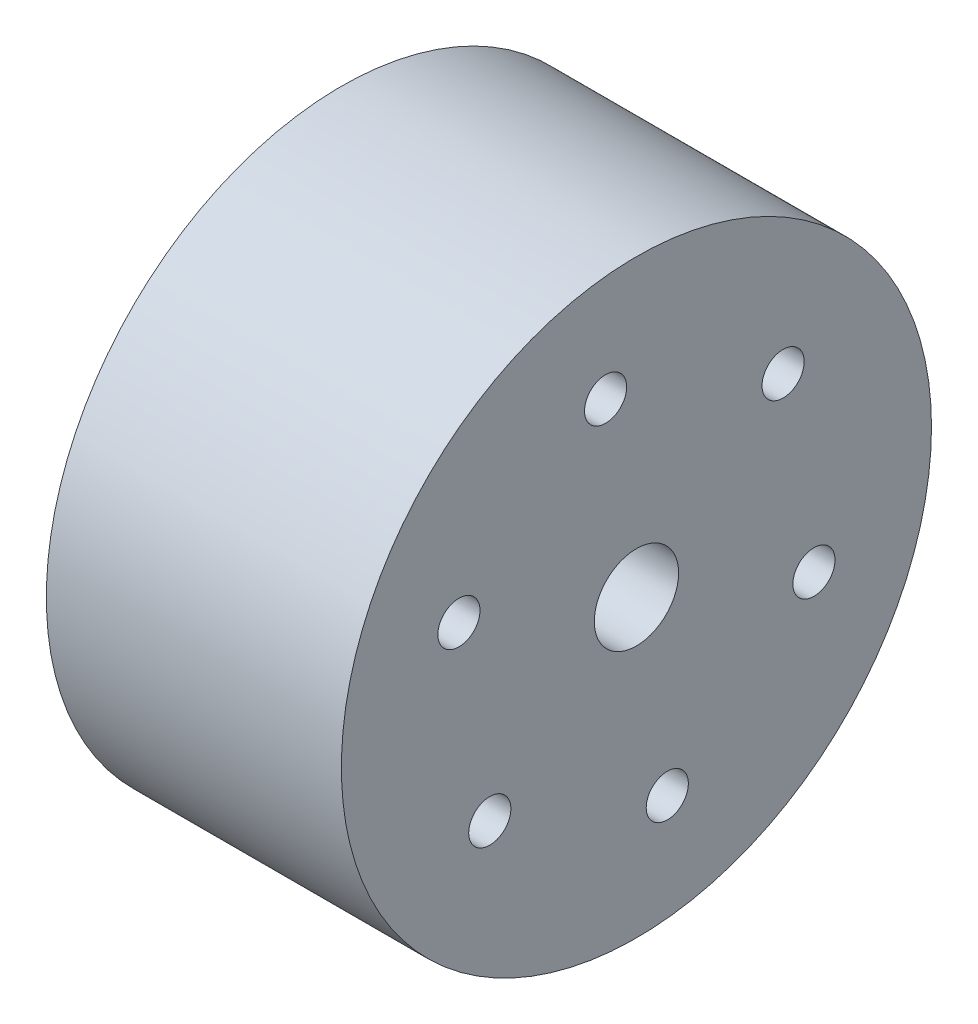
SolidWorks part; units mm, degrees
ref_plane "Front Plane" through (0, 0, 0) normal (0, 0, 1) x (1, 0, 0)
ref_plane "Top Plane" through (0, 0, 0) normal (0, 1, 0) x (1, 0, 0)
ref_plane "Right Plane" through (0, 0, 0) normal (1, 0, 0) x (0, 0, -1)
sketch "Sketch1" plane through (0, 0, 0) normal (0, 0, 1) x (1, 0, 0)
  line L0 (-38.7161, 35) -> (-38.7161, 16)
  line L1 (-38.7161, 16) -> (-33.7161, 16)
  line L2 (-33.7161, 16) -> (-33.7161, 5)
  line L3 (-33.7161, 5) -> (-3.7161, 5)
  line L4 (-3.7161, 5) -> (-3.7161, 35)
  line L5 (-3.7161, 35) -> (-38.7161, 35)
  line L6 (-38.7161, -33) -> (-38.7161, 33) construction
  line L9 (0, 0) -> (-3.7161, 0) construction
  line L10 (-33.7161, -16) -> (-33.7161, 16) construction
  line L13 (0, 0) -> (-58.1661, 0) construction
  dimension "D1" = 35
  dimension "D2" = 30
  dimension "D3" = 32
revolve "Revolve1" add sketch "Sketch1" angle 360 about L9
sketch "Sketch2" plane through (-38.7161, 0, 0) normal (-1, 0, 0) x (0, 0, 1)
  circle A0 centre (21.0557, 7.9314) radius 2.5
  circle A2 centre (17.3966, -14.2691) radius 2.5
  circle A3 centre (-3.6591, -22.2005) radius 2.5
  circle A4 centre (-21.0557, -7.9314) radius 2.5
  circle A5 centre (-17.3966, 14.2691) radius 2.5
  circle A6 centre (3.6591, 22.2005) radius 2.5
  circle A9 centre (21.0557, 7.9314) radius 2.5 construction
  point P20 (0, 0)
  dimension "D1" = 6
extrude "Cut-Extrude1" cut sketch "Sketch2" against normal up to surface (35 mm away) up to face at (-3.7161, 0, -35)
